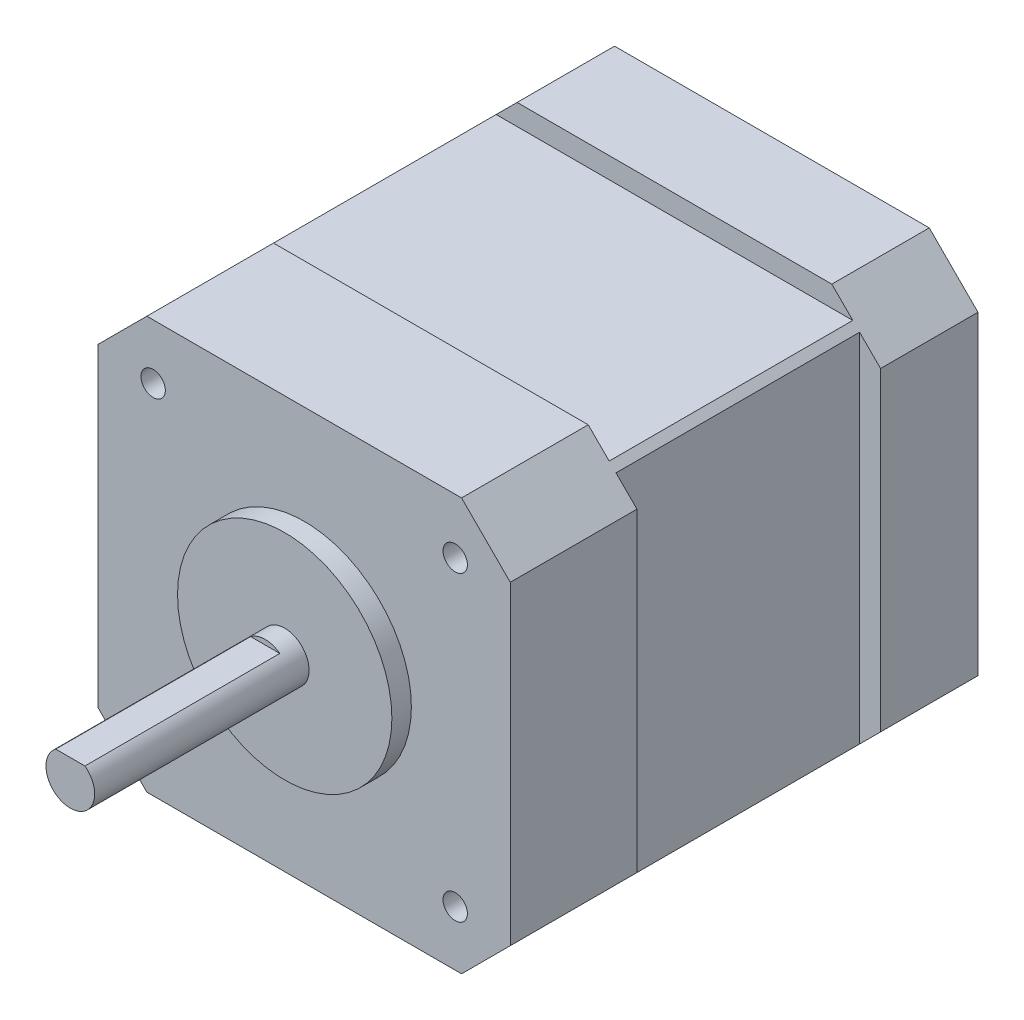
SolidWorks part; units mm, degrees
material "1060 合金"
ref_plane "前视基准面" through (0, 0, 0) normal (0, 0, 1) x (1, 0, 0)
ref_plane "上视基准面" through (0, 0, 0) normal (0, 1, 0) x (1, 0, 0)
ref_plane "右视基准面" through (0, 0, 0) normal (1, 0, 0) x (0, 0, -1)
sketch "草图1" plane through (0, 0, 0) normal (0, 0, 1) x (1, 0, 0)
  line L1 (0, 0) -> (42.3, 0)
  line L2 (0, 0) -> (0, -42.3)
  line L3 (0, -42.3) -> (42.3, -42.3)
  line L4 (42.3, 0) -> (42.3, -42.3)
  dimension "D1" = 42.3
  dimension "D2" = 42.3
extrude "凸台-拉伸1" add sketch "草图1" along normal blind 48
sketch "草图2" plane through (0, 0, 48) normal (0, 0, 1) x (1, 0, 0)
  line L0 (0, 0) -> (42.3, -42.3) construction
  circle A0 centre (21.15, -21.15) radius 11
  dimension "D1" = 22
extrude "凸台-拉伸2" add sketch "草图2" along normal blind 2
sketch "草图3" plane through (0, 0, 50) normal (0, 0, 1) x (1, 0, 0)
  circle A0 centre (21.15, -21.15) radius 2.5
  dimension "D1" = 5
extrude "凸台-拉伸3" add sketch "草图3" along normal blind 22
sketch "草图4" plane through (0, 0, 0) normal (0, 0, -1) x (-1, 0, 0)
  line L0 (-21.15, 0) -> (-21.15, -21.15) construction
  line L1 (-42.3, 0) -> (0, 0) construction
  line L2 (-21.15, -21.15) -> (0, -21.15) construction
  line L3 (0, 0) -> (0, -42.3) construction
  circle A0 centre (-42.3, 0) radius 11
  circle A1 centre (0, 0) radius 11
  circle A2 centre (0, -42.3) radius 11
  circle A3 centre (-42.3, -42.3) radius 11
  point P3 (-21.15, -21.15)
  dimension "D2" = 22
  dimension "D1" = 4
extrude "切除-拉伸1" [suppressed] cut sketch "草图4" against normal blind 42
chamfer "倒角1" distance 5 angle 45 4 edges at (42.3, -42.3, 24) (0, -42.3, 24) (0, 0, 24) (42.3, 0, 24)
sketch "草图5" plane through (0, 0, 48) normal (0, 0, 1) x (1, 0, 0)
  line L0 (21.15, -21.15) -> (21.15, -5.65) construction
  line L1 (5.65, -5.65) -> (36.65, -5.65) construction
  line L2 (5.65, -5.65) -> (5.65, -36.65) construction
  line L3 (5.65, -36.65) -> (36.65, -36.65) construction
  line L4 (36.65, -5.65) -> (36.65, -36.65) construction
  line L5 (21.15, -21.15) -> (36.65, -21.15) construction
  dimension "D1" = 31
  dimension "D2" = 31
hole_wizard "M3 螺纹孔1" positions "3D草图1" profile "草图6" tap size "M3" standard "ISO"
sketch3d "3D草图1"
  point P0 (5.65, -5.65, 48)
  point P3 (5.65, -36.65, 48)
  point P6 (36.65, -36.65, 48)
  point P9 (36.65, -5.65, 48)
sketch "草图6" plane through (5.65, -5.65, 48) normal (1, 0, 0) x (0, -1, 0)
  line L0 (0, 0) -> (0, 6.7511)
  line L1 (0, 6.7511) -> (1.25, 6)
  line L2 (1.25, 6) -> (1.25, 0)
  line L5 (1.25, 0) -> (0, 0)
  line L10 (0, 6.7511) -> (-1.25, 6) construction
  line L11 (0, -6.35) -> (0, 107.95) construction
  dimension "螺纹孔钻头直径" = 2.5
  dimension "螺纹孔钻头深度" = 6
  dimension "导头角度" = 118
cosmetic thread "孔螺蚊线1" parameters "D1"=4, "D2"=3
cosmetic thread "孔螺蚊线2" parameters "D1"=4, "D2"=3
cosmetic thread "孔螺蚊线3" parameters "D1"=4, "D2"=3
cosmetic thread "孔螺蚊线4" parameters "D1"=4, "D2"=3
fillet "圆角1" [suppressed] radius 1
ref_plane "基准面1" through (0, 0, 10) normal (0, 0, -1) x (-1, 0, 0)
sketch "草图7" plane through (0, 0, 10) normal (0, 0, -1) x (-1, 0, 0)
  line L0 (-21.15, 0) -> (-21.15, -2.15) construction
  line L1 (-40.15, -2.15) -> (-2.15, -2.15)
  line L2 (-40.15, -2.15) -> (-40.15, -40.15)
  line L3 (-40.15, -40.15) -> (-2.15, -40.15)
  line L4 (-2.15, -2.15) -> (-2.15, -40.15)
  line L5 (-37.3, 0) -> (-5, 0) construction
  line L6 (0, -21.15) -> (-2.15, -21.15) construction
  line L7 (0, -5) -> (0, -37.3) construction
  dimension "D1" = 38
  dimension "D2" = 38
extrude "切除-拉伸2" cut sketch "草图7" against normal blind 25 flip side to cut
sketch "草图8" plane through (0, 0, 72) normal (0, 0, 1) x (1, 0, 0)
  line L1 (18.3315, -17.158) -> (25.0318, -17.158)
  line L2 (18.3315, -17.158) -> (18.3315, -19.15)
  line L3 (18.3315, -19.15) -> (25.0318, -19.15)
  line L4 (25.0318, -17.158) -> (25.0318, -19.15)
  circle A0 centre (21.15, -21.15) radius 2.5 construction
  dimension "D1" = 2
extrude "切除-拉伸3" cut sketch "草图8" against normal blind 20
